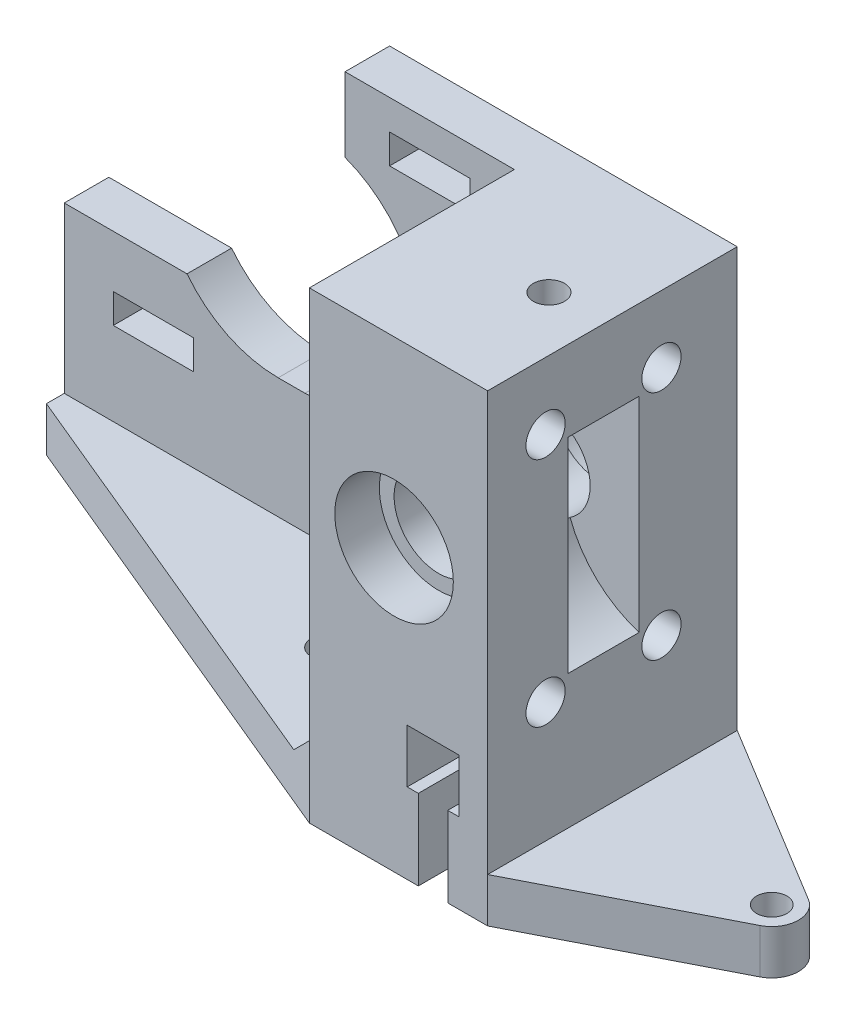
SolidWorks part; units mm, degrees
ref_plane "Front Plane" through (0, 0, 0) normal (0, 0, 1) x (1, 0, 0)
ref_plane "Top Plane" through (0, 0, 0) normal (0, 1, 0) x (1, 0, 0)
ref_plane "Right Plane" through (0, 0, 0) normal (1, 0, 0) x (0, 0, -1)
sketch "Sketch1" plane through (0, 0, 0) normal (0, 0, 1) x (1, 0, 0)
  line L0 (0, 0) -> (-60, 0) construction
  line L1 (-60, -31.5) -> (10.5, -31.5)
  line L2 (-60, -31.5) -> (-60, -8)
  line L3 (-28.5, 20.5) -> (10.5, 20.5)
  line L4 (10.5, -31.5) -> (10.5, 20.5)
  line L5 (-34.5, 0) -> (-34.5, -31.5) construction
  line L6 (-19, -15.5) -> (-19, 17.15) construction
  line L7 (-14.5, 15.5) -> (-50, 15.5) construction
  line L8 (-23.5, 13.85) -> (-14.5, 13.85)
  line L9 (-23.5, 13.85) -> (-23.5, 17.15)
  line L10 (-23.5, 17.15) -> (-14.5, 17.15)
  line L11 (-14.5, 13.85) -> (-14.5, 17.15)
  line L12 (-36, -12.9851) -> (-33, -12.9851)
  line L14 (-14.5, -13.85) -> (-14.5, -17.15)
  line L15 (-23.5, -17.15) -> (-14.5, -17.15)
  line L16 (-23.5, -13.85) -> (-23.5, -17.15)
  line L17 (-23.5, -13.85) -> (-14.5, -13.85)
  line L18 (-45.5, -13.85) -> (-54.5, -13.85)
  line L19 (-45.5, -13.85) -> (-45.5, -17.15)
  line L20 (-45.5, -17.15) -> (-54.5, -17.15)
  line L21 (-54.5, -13.85) -> (-54.5, -17.15)
  line L26 (-28.5, 20.5) -> (-28.5, 12.1804)
  line L27 (-60, -8) -> (-46.228, -8)
  line L28 (-50, -15.5) -> (-19, -15.5) [skipped]
  line L29 (-50, 15.5) -> (-50, -15.5) [skipped]
  circle A0 centre (0, 0) radius 5
  circle A1 centre (-34.5, 0) radius 15.5 construction
  arc A2 (-46.228, -8) -> (-36, -12.9851) centre (-36, 0) ccw
  arc A4 (-33, -12.9851) -> (-28.5, 12.1804) centre (-33, 0) ccw
  dimension "D1" = 10
  dimension "D6" = 34.5
  dimension "D8" = 3.3
  dimension "D2" = 31
  dimension "D7" = 6
  dimension "D3" = 52
  dimension "D4" = 60
  dimension "D5" = 31.5
  dimension "D9" = 9
  dimension "D10" = 3
  dimension "D11" = 1.5
  dimension "D12" = 8
  dimension "D13" = 10.5
extrude "Boss-Extrude1" add sketch "Sketch1" along normal blind 28
sketch "Sketch2" plane through (0, 0, 28) normal (0, 0, 1) x (1, 0, 0)
  line L0 (-60, -8) -> (-60, -31.5) construction
  line L1 (-60, -26.5) -> (-9.5, -26.5)
  line L2 (-60, -26.5) -> (-60, 20.5)
  line L3 (-60, 20.5) -> (-9.5, 20.5)
  line L4 (-9.5, -26.5) -> (-9.5, 20.5)
  line L5 (10.5, 20.5) -> (-28.5, 20.5) construction
  line L6 (0, 0) -> (-60, 0) construction
  circle A0 centre (-34.5, 0) radius 17.3693 construction
  dimension "D1" = 25
  dimension "D2" = 26.5
  dimension "D3" = 34.5
extrude "Cut-Extrude1" cut sketch "Sketch2" against normal offset from surface (23 mm away) 5 up to face at (-19, -15.5, 0)
sketch "Sketch3" plane through (0, 0, 28) normal (0, 0, 1) x (1, 0, 0)
  circle A0 centre (0, 0) radius 6.65
  dimension "D1" = 13.3
extrude "Cut-Extrude2" cut sketch "Sketch3" against normal blind 5
sketch "Sketch4" plane through (0, 0, 0) normal (0, 0, -1) x (-1, 0, 0)
  circle A0 centre (0, 0) radius 6.65
  dimension "D1" = 13.3
extrude "Cut-Extrude3" cut sketch "Sketch4" against normal blind 5
ref_plane "Plane1" through (0, 0, 11) normal (0, 0, 1) x (1, 0, 0)
sketch "Sketch5" plane through (0, 0, 11) normal (0, 0, 1) x (1, 0, 0)
  line L0 (0, 0) -> (14, 0) construction
  circle A0 centre (14, 0) radius 12
  dimension "D2" = 24
  dimension "D1" = 14
extrude "Cut-Extrude4" cut sketch "Sketch5" along normal blind 8
ref_plane "Plane2" through (0, -22.5, 0) normal (0, -1, 0) x (1, 0, 0)
sketch "Sketch6" plane through (0, -31.5, 0) normal (0, -1, 0) x (1, 0, 0)
  line L0 (0, 23) -> (0, 5) construction
  line L1 (5, 23) -> (-5, 23) construction
  line L2 (-6.65, 5) -> (6.65, 5) construction
  line L3 (10.5, 15) -> (2.75, 15) construction
  line L4 (10.5, 28) -> (10.5, 0) construction
  line L6 (2.75, 19) -> (2.75, 11) construction
  line L7 (2.725, 15) -> (2.725, 28)
  line L8 (-60, 28) -> (10.5, 28) construction
  line L9 (2.725, 28) -> (6.025, 28)
  line L10 (6.025, 28) -> (6.025, 15)
  arc A0 (2.725, 15) -> (6.025, 15) centre (4.375, 15) ccw
  dimension "D1" = 1.65
  dimension "D2" = 4.375
extrude "Cut-Extrude5" cut sketch "Sketch6" against normal up to surface (9 mm away)
sketch "Sketch7" plane through (0, -22.5, 0) normal (0, -1, 0) x (1, 0, 0)
  line L0 (1.475, 28) -> (7.275, 28)
  line L2 (1.475, 28) -> (1.475, 13.3257)
  line L3 (1.475, 13.3257) -> (4.375, 11.6514)
  line L4 (4.375, 11.6514) -> (7.275, 13.3257)
  line L5 (7.275, 13.3257) -> (7.275, 28)
  line L7 (-60, 28) -> (2.725, 28) construction
  line L8 (6.025, 28) -> (10.5, 28) construction
  line L10 (3.7855, 18.0083) -> (1.1307, 16.4755) [skipped]
  line L11 (6.6855, 17.0147) -> (4.0307, 18.5474) [skipped]
  circle A0 centre (4.375, 15) radius 2.9 construction
  arc A1 (2.725, 15) -> (6.025, 15) centre (4.375, 15) ccw construction
  dimension "D1" = 5.8
extrude "Cut-Extrude6" cut sketch "Sketch7" against normal blind 6
sketch "Sketch8" plane through (0, -31.5, 0) normal (0, -1, 0) x (1, 0, 0)
  circle A0 centre (4.375, 15) radius 1.15
  arc A1 (2.725, 15) -> (6.025, 15) centre (4.375, 15) ccw construction
  dimension "D1" = 2.3
extrude "Cut-Extrude7" cut sketch "Sketch8" against normal through all
chamfer "Chamfer1" distance 21 distance2 50.5 1 edges at (-60, -29, 28)
sketch "Sketch9" plane through (10.5, 0, 0) normal (1, 0, 0) x (0, 0, -1)
  line L0 (-15, 11.4782) -> (-15, 17.5944) construction
  line L1 (-11, 11.4782) -> (-19, 11.4782) construction
  line L2 (0, 0) -> (-25.9492, 0) construction
  circle A0 centre (-8.5, 13) radius 2.2
  circle A1 centre (-21.5, 13) radius 2.2
  circle A2 centre (-8.5, -13) radius 2.2
  circle A3 centre (-21.5, -13) radius 2.2
  dimension "D1" = 4.4
  dimension "D2" = 6.5
  dimension "D3" = 13
extrude "Cut-Extrude8" cut sketch "Sketch9" against normal through all
sketch "Sketch10" plane through (-9.5, 0, 0) normal (-1, 0, 0) x (0, 0, 1)
  line L1 (4.85, 15.1073) -> (4.85, 10.8927)
  line L2 (4.85, 10.8927) -> (8.5, 8.7853)
  line L3 (8.5, 8.7853) -> (12.15, 10.8927)
  line L4 (12.15, 10.8927) -> (12.15, 15.1073)
  line L5 (12.15, 15.1073) -> (8.5, 17.2147)
  line L6 (8.5, 17.2147) -> (4.85, 15.1073)
  line L7 (25.15, 10.8927) -> (25.15, 15.1073)
  line L8 (25.15, 15.1073) -> (21.5, 17.2147)
  line L9 (21.5, 17.2147) -> (17.85, 15.1073)
  line L10 (17.85, 15.1073) -> (17.85, 10.8927)
  line L11 (17.85, 10.8927) -> (21.5, 8.7853)
  line L12 (21.5, 8.7853) -> (25.15, 10.8927)
  line L13 (25.15, -10.8927) -> (21.5, -8.7853)
  line L14 (21.5, -8.7853) -> (17.85, -10.8927)
  line L15 (17.85, -10.8927) -> (17.85, -15.1073)
  line L16 (17.85, -15.1073) -> (21.5, -17.2147)
  line L17 (21.5, -17.2147) -> (25.15, -15.1073)
  line L18 (25.15, -15.1073) -> (25.15, -10.8927)
  line L19 (12.15, -10.8927) -> (8.5, -8.7853)
  line L20 (8.5, -8.7853) -> (4.85, -10.8927)
  line L21 (4.85, -10.8927) -> (4.85, -15.1073)
  line L22 (4.85, -15.1073) -> (8.5, -17.2147)
  line L23 (8.5, -17.2147) -> (12.15, -15.1073)
  line L24 (12.15, -15.1073) -> (12.15, -10.8927)
  circle A0 centre (8.5, 13) radius 3.65 construction
  circle A1 centre (8.5, 13) radius 2.2 construction
  circle A2 centre (21.5, 13) radius 3.65 construction
  circle A3 centre (21.5, -13) radius 3.65 construction
  circle A4 centre (8.5, -13) radius 3.65 construction
  circle A5 centre (21.5, 13) radius 2.2 construction
  circle A6 centre (21.5, -13) radius 2.2 construction
  circle A7 centre (8.5, -13) radius 2.2 construction
  dimension "D1" = 7.3
extrude "Cut-Extrude9" cut sketch "Sketch10" against normal blind 7 and the other way blind 3
sketch "Sketch11" plane through (10.5, 0, 0) normal (1, 0, 0) x (0, 0, -1)
  line L0 (-28, -31.5) -> (0, -31.5) construction
  line L1 (0, -31.5) -> (-7, -31.5)
  line L2 (0, -31.5) -> (0, -41.5)
  line L3 (0, -41.5) -> (-7, -41.5)
  line L5 (-5, -36.5) -> (0, -36.5) construction
  line L6 (-5, -39.7) -> (-7, -39.7)
  line L7 (-7, -39.7) -> (-7, -41.5)
  line L8 (-5, -33.3) -> (-7, -33.3)
  line L9 (-7, -33.3) -> (-7, -31.5)
  arc A0 (-5, -39.7) -> (-5, -33.3) centre (-5, -36.5) ccw
  dimension "D1" = 3.2
  dimension "D2" = 10
  dimension "D3" = 2
  dimension "D4" = 5
extrude "Boss-Extrude2" [suppressed] add sketch "Sketch11" against normal blind 10
pattern_linear "LPattern1" [suppressed] count 2 spacing 60.5
sketch "Sketch12" plane through (0, 20.5, 0) normal (0, 1, 0) x (1, 0, 0)
  circle A0 centre (4.375, -15) radius 1.75
  circle A1 centre (4.375, -15) radius 1.15 construction
  dimension "D1" = 3.5
extrude "Cut-Extrude10" cut sketch "Sketch12" against normal blind 10
chamfer "Chamfer2" distance 3 angle 45 1 edges at (-9.5, -26.5, 16.5)
chamfer "Chamfer3" [suppressed] distance 1.8 angle 45
sketch "Sketch14" plane through (0, -31.5, 0) normal (0, -1, 0) x (1, 0, 0)
  line L0 (10.5, 0) -> (30.9347, 12.4373)
  line L2 (30.7386, 17.6722) -> (10.5, 28)
  line L3 (10.5, 28) -> (10.5, 0)
  line L4 (4.375, 15) -> (29.375, 15) construction
  arc A0 (30.9347, 12.4373) -> (30.7386, 17.6722) centre (29.375, 15) ccw
  dimension "D1" = 3
  dimension "D2" = 25
extrude "Boss-Extrude3" add sketch "Sketch14" against normal up to surface (5 mm away) up to face at (-36.25, -26.5, 10.9381)
sketch "Sketch15" plane through (0, -31.5, 0) normal (0, -1, 0) x (1, 0, 0)
  line L0 (-20.625, 15) -> (29.375, 15) construction
  circle A1 centre (-20.625, 15) radius 1.7
  circle A2 centre (29.375, 15) radius 1.7
  point P4 (4.375, 15)
  dimension "D2" = 3.4
  dimension "D1" = 50
extrude "Cut-Extrude11" cut sketch "Sketch15" against normal through all
